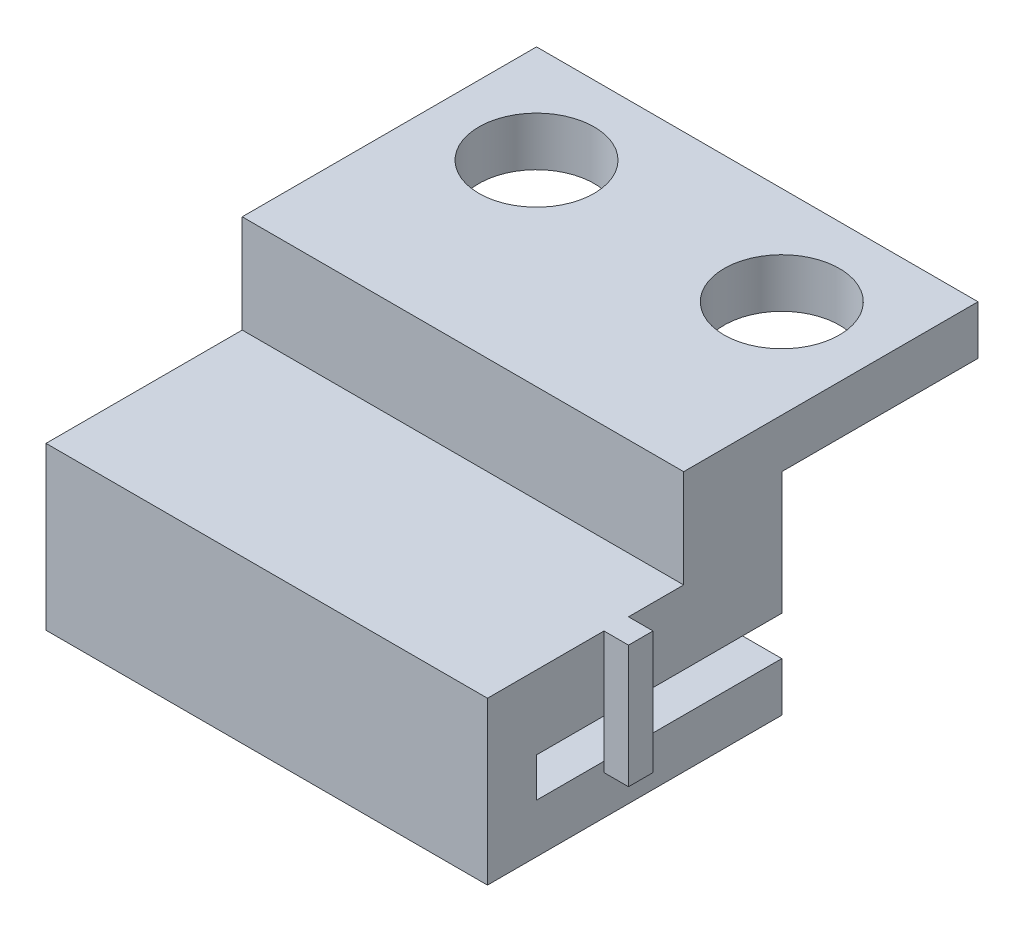
SolidWorks part; units mm, degrees
ref_plane "Front Plane" through (0, 0, 0) normal (0, 0, 1) x (1, 0, 0)
ref_plane "Top Plane" through (0, 0, 0) normal (0, 1, 0) x (1, 0, 0)
ref_plane "Right Plane" through (0, 0, 0) normal (1, 0, 0) x (0, 0, -1)
sketch "Sketch1" plane through (0, 0, 0) normal (0, 1, 0) x (1, 0, 0)
  line L0 (-5, 0) -> (5, 0) construction
  line L1 (-9, 4) -> (9, 4)
  line L2 (-9, 4) -> (-9, -8)
  line L3 (-9, -8) -> (9, -8)
  line L4 (9, 4) -> (9, -8)
  circle A0 centre (-5, 0) radius 2.35
  circle A1 centre (5, 0) radius 2.35
  point P8 (0, 0)
  point P9 (0, 4)
  dimension "D3" = 4.7
  dimension "D1" = 10
  dimension "D2" = 18
  dimension "D4" = 12
  dimension "D5" = 4
extrude "Boss-Extrude1" add sketch "Sketch1" along normal blind 2
sketch "Sketch2" plane through (9, 0, 0) normal (1, 0, 0) x (0, 0, -1)
  line L4 (-8, 0) -> (-8, -2)
  line L5 (-8, -2) -> (-16, -2)
  line L6 (-16, -2) -> (-16, -8.6)
  line L8 (-8, 0) -> (4, 0)
  line L9 (4, 0) -> (4, 2)
  line L10 (4, 2) -> (-8, 2)
  line L11 (-8, 2) -> (-8, 0)
  line L12 (-8, 0) -> (4, 0)
  line L13 (4, 0) -> (4, 2)
  line L14 (4, 2) -> (-8, 2)
  line L15 (-8, 2) -> (-8, 0)
  line L16 (-14, -6.6) -> (-14, -5)
  line L17 (-14, -5) -> (-4, -5)
  line L18 (-4, -5) -> (-4, 0)
  line L19 (-4, 0) -> (-8, 0)
  line L20 (-14, -6.6) -> (-4, -6.6)
  line L21 (-4, -6.6) -> (-4, -8.6)
  line L22 (-4, -8.6) -> (-16, -8.6)
  point P7 (0, 0)
  point P15 (-21, -9.2746)
  dimension "D2" = 10
  dimension "D3" = 4
  dimension "D4" = 5
  dimension "D5" = 8
  dimension "D6" = 1.6
  dimension "D7" = 3
  dimension "D8" = 2
  dimension "D1" = 0
extrude "Boss-Extrude2" add sketch "Sketch2" against normal up to surface (18 mm away) up to face at (-9, 1, 2)
sketch "Sketch3" plane through (0, -2, 0) normal (0, 1, 0) x (1, 0, 0)
  line L0 (9, -8) -> (9, -16) construction
  line L1 (9, -10.25) -> (10, -10.25)
  line L2 (9, -10.25) -> (9, -11.25)
  line L3 (9, -11.25) -> (10, -11.25)
  line L4 (10, -10.25) -> (10, -11.25)
  circle A1 centre (5, 0) radius 2.35 construction
  circle A2 centre (5, 0) radius 2.35 construction
  line M7 (9, -16) -> (9, -8)
  dimension "D1" = 1
  dimension "D2" = 1
  dimension "D3" = 10.25
extrude "Boss-Extrude3" add sketch "Sketch3" against normal blind 5 contours L4 L1 L3 M7
